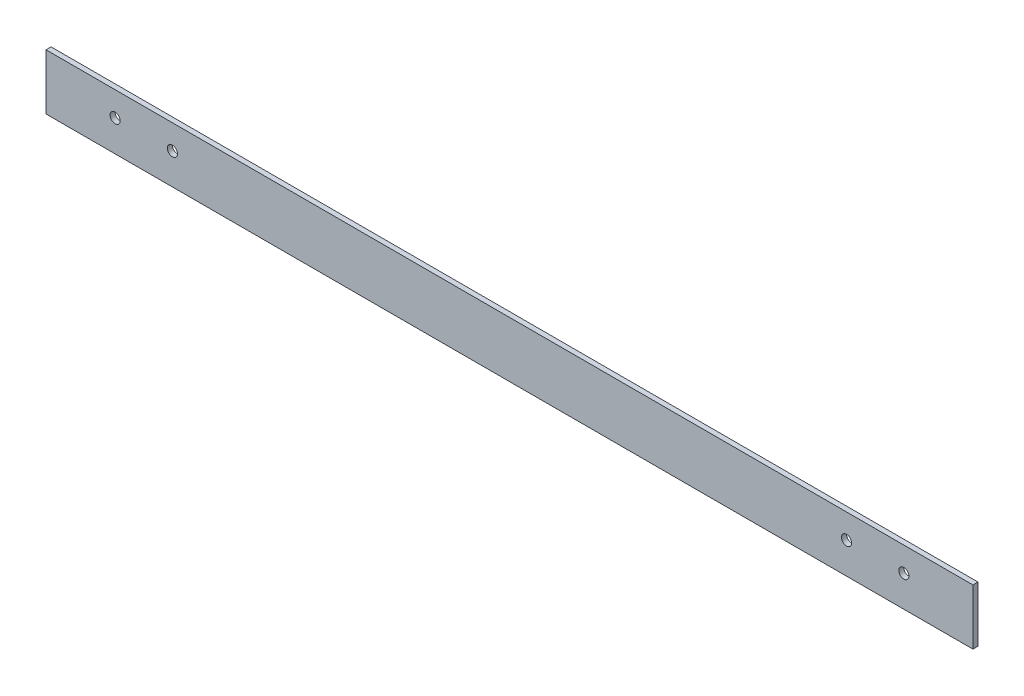
SolidWorks part; units mm, degrees
ref_plane "前视基准面" through (0, 0, 0) normal (0, 0, 1) x (1, 0, 0)
ref_plane "上视基准面" through (0, 0, 0) normal (0, 1, 0) x (1, 0, 0)
ref_plane "右视基准面" through (0, 0, 0) normal (1, 0, 0) x (0, 0, -1)
sketch "草图1" plane through (0, 0, 0) normal (0, 0, 1) x (1, 0, 0)
  line L1 (-275, 16.5) -> (275, 16.5)
  line L2 (-275, 16.5) -> (-275, -16.5)
  line L3 (-275, -16.5) -> (275, -16.5)
  line L4 (275, 16.5) -> (275, -16.5)
  point P4 (0, 16.5)
  point P7 (275, 0)
  dimension "D1" = 550
  dimension "D2" = 33
extrude "凸台-拉伸1" add sketch "草图1" along normal blind 3
sketch "草图2" plane through (0, 0, 0) normal (0, 0, 1) x (1, 0, 0)
  line L0 (-275, -16.5) -> (275, -16.5) construction
  line L1 (0, -16.5) -> (0, 16.5) construction
  line L2 (275, 16.5) -> (-275, 16.5) construction
  circle A0 centre (-234, 2) radius 3
  circle A1 centre (-200, 2) radius 3
  circle A2 centre (200, 2) radius 3
  circle A3 centre (234, 2) radius 3
  dimension "D3" = 6
  dimension "D1" = 200
  dimension "D2" = 34
  dimension "D4" = 18.5
extrude "切除-拉伸1" cut sketch "草图2" along normal through all
